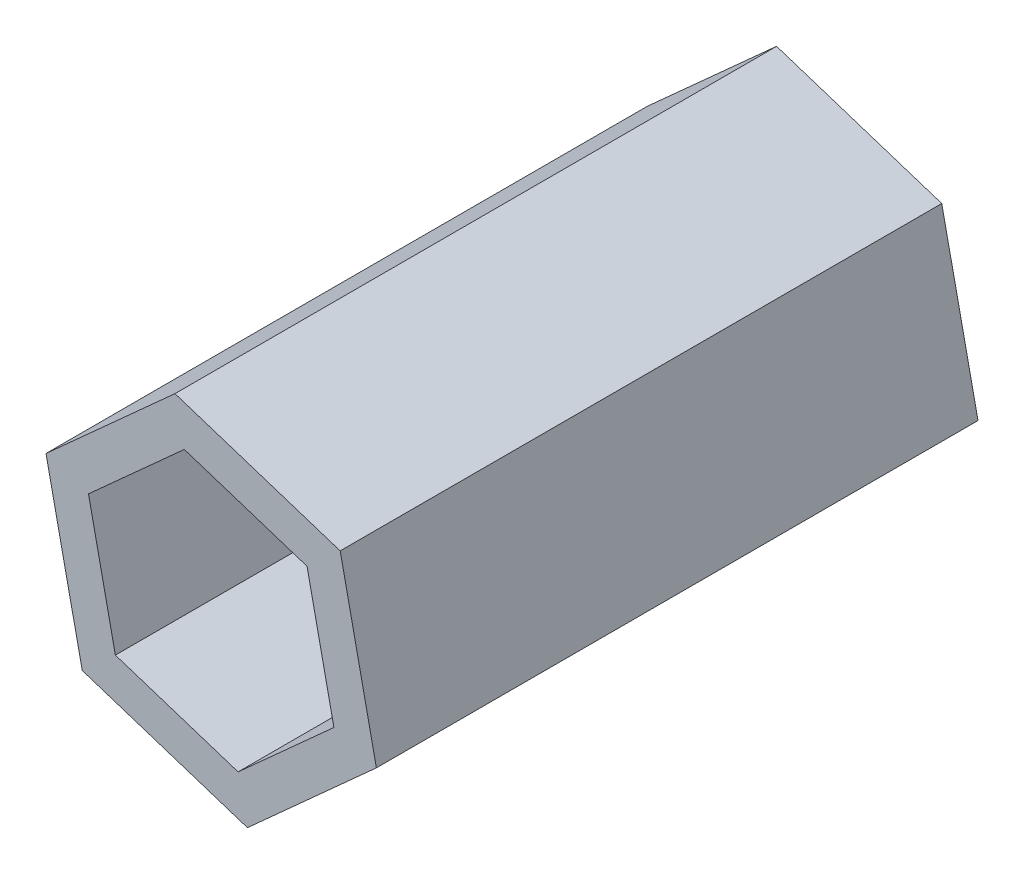
SolidWorks part; units mm, degrees
ref_plane "Plano frontal" through (0, 0, 0) normal (0, 0, 1) x (1, 0, 0)
ref_plane "Plano superior" through (0, 0, 0) normal (0, 1, 0) x (1, 0, 0)
ref_plane "Plano direito" through (0, 0, 0) normal (1, 0, 0) x (0, 0, -1)
sketch "Esboço1" plane through (0, 0, 0) normal (0, 0, 1) x (1, 0, 0)
  line L7 (-0.8428, 3.9526) -> (-3.8444, 1.2464)
  line L8 (-3.8444, 1.2464) -> (-3.0017, -2.7062)
  line L9 (-3.0017, -2.7062) -> (0.8428, -3.9526)
  line L10 (0.8428, -3.9526) -> (3.8444, -1.2464)
  line L11 (3.8444, -1.2464) -> (3.0017, 2.7062)
  line L12 (3.0017, 2.7062) -> (-0.8428, 3.9526)
  circle A1 centre (0, 0) radius 3.5 construction
  dimension "D2" = 7
extrude "Ressalto-extrusão1" add sketch "Esboço1" along normal blind 14
sketch "Esboço2" plane through (0, 0, 14) normal (0, 0, 1) x (1, 0, 0)
  line L1 (2.2298, 2.0103) -> (-0.6261, 2.9362)
  line L2 (-0.6261, 2.9362) -> (-2.8559, 0.9259)
  line L3 (-2.8559, 0.9259) -> (-2.2298, -2.0103)
  line L4 (-2.2298, -2.0103) -> (0.6261, -2.9362)
  line L5 (0.6261, -2.9362) -> (2.8559, -0.9259)
  line L6 (2.8559, -0.9259) -> (2.2298, 2.0103)
  circle A0 centre (0, 0) radius 2.6 construction
  dimension "D1" = 5.2
extrude "Corte-extrusão1" cut sketch "Esboço2" against normal blind 10.6
sketch "Esboço3" plane through (0, 0, 0) normal (0, 0, -1) x (-1, 0, 0)
  circle A0 centre (0, 0) radius 0.75
extrude "Corte-extrusão2" cut sketch "Esboço3" against normal up to next
